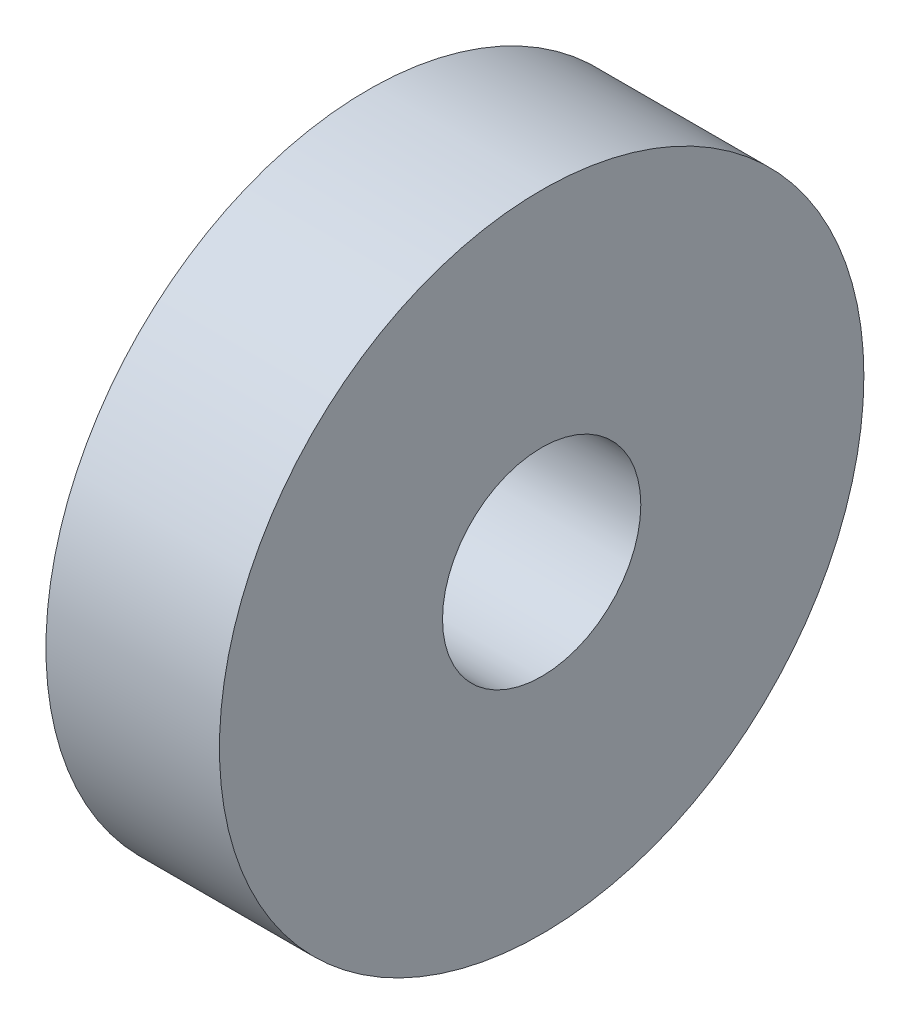
SolidWorks part; units mm, degrees
ref_plane "Спереди" through (0, 0, 0) normal (0, 0, 1) x (1, 0, 0)
ref_plane "Сверху" through (0, 0, 0) normal (0, 1, 0) x (1, 0, 0)
ref_plane "Справа" through (0, 0, 0) normal (1, 0, 0) x (0, 0, -1)
sketch "Эскиз1" plane through (0, 0, 0) normal (1, 0, 0) x (0, 0, -1)
  circle A0 centre (0, 0) radius 4
  circle A1 centre (0, 0) radius 13
extrude "Вытянуть1" add sketch "Эскиз1" against normal blind 7
